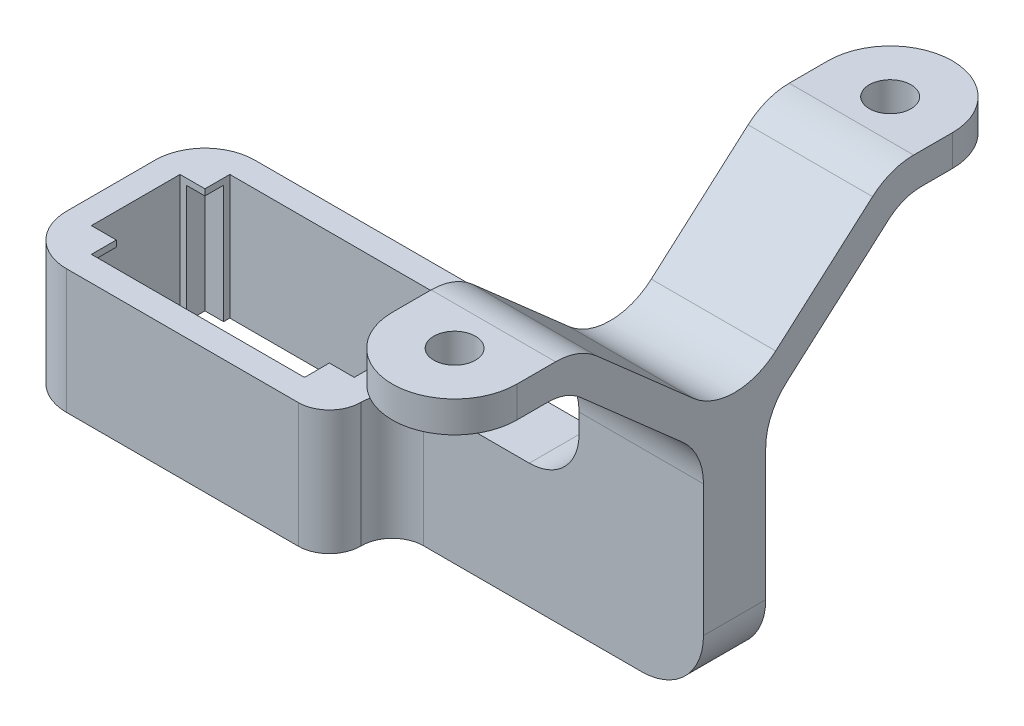
SolidWorks part; units mm, degrees
material "Nylon 101"
ref_plane "Front Plane" through (0, 0, 0) normal (0, 0, 1) x (1, 0, 0)
ref_plane "Top Plane" through (0, 0, 0) normal (0, 1, 0) x (1, 0, 0)
ref_plane "Right Plane" through (0, 0, 0) normal (1, 0, 0) x (0, 0, -1)
sketch "Sketch1" plane through (0, 20.13, 0) normal (0, 1, 0) x (1, 0, 0)
  line L0 (20.125, 10.125) -> (17.125, 10.125)
  line L1 (-20.125, 10.125) -> (-20.125, 7.125)
  line L2 (-20.125, -10.125) -> (-17.125, -10.125)
  line L3 (20.125, -10.125) -> (20.125, -7.125)
  line L4 (20.075, -10.075) -> (20.075, 10.075)
  line L5 (20.075, 10.075) -> (-20.075, 10.075)
  line L6 (-20.075, 10.075) -> (-20.075, -10.075)
  line L7 (-20.075, -10.075) -> (20.075, -10.075)
  line L10 (-20.075, 10.075) -> (-20.075, -10.075) construction
  line L12 (25.125, -15.125) -> (25.125, 15.125)
  line L13 (25.125, 15.125) -> (-25.125, 15.125)
  line L14 (-25.125, 15.125) -> (-25.125, -15.125)
  line L15 (-25.125, -15.125) -> (25.125, -15.125)
  line L16 (20.125, 7.125) -> (20.125, 10.125)
  line L17 (20.125, 7.125) -> (21.125, 7.125)
  line L19 (20.125, -7.125) -> (21.125, -7.125)
  line L20 (21.125, 7.125) -> (21.125, -7.125)
  line L21 (-20.125, 7.125) -> (-21.125, 7.125)
  line L23 (-20.125, -7.125) -> (-21.125, -7.125)
  line L24 (-21.125, 7.125) -> (-21.125, -7.125)
  line L26 (-17.125, 10.125) -> (-17.125, 11.125)
  line L27 (-17.125, 11.125) -> (17.125, 11.125)
  line L28 (17.125, 10.125) -> (17.125, 11.125)
  line L30 (17.125, -10.125) -> (17.125, -11.125)
  line L31 (17.125, -11.125) -> (-17.125, -11.125)
  line L32 (-17.125, -10.125) -> (-17.125, -11.125)
  line L33 (20.075, -10.075) -> (20.075, 10.075) construction
  line L34 (20.125, -10.125) -> (20.125, 10.125) construction
  line L35 (-20.075, -10.075) -> (20.075, -10.075) construction
  line L36 (17.125, -10.125) -> (20.125, -10.125)
  line L37 (-20.125, -10.125) -> (20.125, -10.125) construction
  line L38 (20.075, 10.075) -> (-20.075, 10.075) construction
  line L39 (-17.125, 10.125) -> (-20.125, 10.125)
  line L40 (20.125, 10.125) -> (-20.125, 10.125) construction
  line L41 (-20.125, -7.125) -> (-20.125, -10.125)
  line L42 (-20.125, 10.125) -> (-20.125, -10.125) construction
  dimension "D4" = 1
  dimension "D5" = 3
  dimension "D1" = 0
  dimension "D2" = 0.05
  dimension "D3" = 5
extrude "Boss-Extrude1" add sketch "Sketch1" against normal blind 19 and the other way blind 1
ref_plane "Plane1" through (0, 0, 0) normal (0, 0, 1) x (1, 0, 0)
sketch "Sketch2" plane through (0, 0, 0) normal (0, 0, 1) x (1, 0, 0)
  line L0 (25.125, 21.13) -> (55.125, 21.13)
  line L1 (55.125, 21.13) -> (55.125, 61.13)
  line L2 (55.125, 61.13) -> (75.125, 61.13)
  line L3 (75.125, 61.13) -> (75.125, 1.13)
  line L4 (75.125, 1.13) -> (25.125, 1.13)
  line L5 (25.125, 1.13) -> (25.125, 21.13) construction
  line L6 (25.125, 21.13) -> (25.125, 1.13)
  dimension "D1" = 50
  dimension "D2" = 60
extrude "Boss-Extrude2" add sketch "Sketch2" against normal mid plane 10
sketch "Sketch3" plane through (0, 61.13, 0) normal (0, 1, 0) x (1, 0, 0)
  line L0 (65.125, 35) -> (65.125, -35) construction
  line L1 (75.125, 35) -> (75.125, -35)
  line L2 (55.125, 35) -> (55.125, -35)
  line L3 (55.125, 5) -> (55.125, -5) construction
  line L6 (65.125, 5) -> (65.125, -5) construction
  line L7 (75.125, 5) -> (55.125, 5) construction
  line L8 (75.125, -5) -> (55.125, -5) construction
  line L9 (75.125, 5) -> (75.125, -5) construction
  line L10 (55.125, 5) -> (55.125, -5)
  line L11 (75.125, 5) -> (75.125, -5)
  arc A0 (75.125, 35) -> (55.125, 35) centre (65.125, 35) ccw
  arc A1 (55.125, -35) -> (75.125, -35) centre (65.125, -35) ccw
  point P2 (65.125, 0)
  point P7 (65.125, 0)
  line M8 (75.125, 5) -> (55.125, 5)
  line M10 (55.125, -5) -> (75.125, -5)
  dimension "D1" = 70
extrude "Boss-Extrude3" add sketch "Sketch3" against normal blind 5 contours L1 A0 L2 M8 | L2 A1 L1 M10
sketch "Sketch4" plane through (0, 56.13, 0) normal (0, -1, 0) x (1, 0, 0)
  circle A0 centre (65.125, 35) radius 3.35
  circle A1 centre (65.125, -35) radius 3.35
  dimension "D1" = 6.7
extrude "Cut-Extrude1" cut sketch "Sketch4" against normal blind 10
sketch "Sketch6" plane through (0, 21.13, 0) normal (0, 1, 0) x (1, 0, 0)
  line L0 (17.125, 11.125) -> (-17.125, 11.125) construction
  line L1 (21.125, 11.125) -> (17.125, 11.125)
  line L2 (21.125, 11.125) -> (21.125, 7.125)
  line L3 (21.125, 7.125) -> (17.125, 7.125)
  line L4 (17.125, 11.125) -> (17.125, 7.125)
  line L5 (21.125, -11.125) -> (17.125, -11.125)
  line L6 (21.125, -11.125) -> (21.125, -7.125)
  line L7 (21.125, -7.125) -> (17.125, -7.125)
  line L8 (17.125, -11.125) -> (17.125, -7.125)
  line L9 (-21.125, -11.125) -> (-17.125, -11.125)
  line L10 (-21.125, -11.125) -> (-21.125, -7.125)
  line L11 (-21.125, -7.125) -> (-17.125, -7.125)
  line L12 (-17.125, -11.125) -> (-17.125, -7.125)
  line L13 (-21.125, 11.125) -> (-17.125, 11.125)
  line L14 (-21.125, 11.125) -> (-21.125, 7.125)
  line L15 (-21.125, 7.125) -> (-17.125, 7.125)
  line L16 (-17.125, 11.125) -> (-17.125, 7.125)
  line L17 (21.125, -7.125) -> (21.125, 7.125) construction
  line L18 (-17.125, -11.125) -> (17.125, -11.125) construction
  line L19 (-21.125, 7.125) -> (-21.125, -7.125) construction
  line L20 (21.125, 7.125) -> (20.125, 7.125) construction
  line L21 (17.125, 10.125) -> (17.125, 11.125) construction
extrude "Boss-Extrude4" add sketch "Sketch6" against normal blind 1
sketch "Sketch10" plane through (0, 1.13, 0) normal (0, -1, 0) x (1, 0, 0)
  line L1 (21.125, 7.125) -> (21.125, -7.125) construction
  line L2 (21.125, 0) -> (24.125, 0) construction
  circle A0 centre (24.125, 0) radius 2
  circle A1 centre (24.125, 0) radius 3.5
  dimension "D1" = 4
  dimension "D2" = 7
  dimension "D3" = 1
hole_wizard "Tap Drill for M4x0.7 Tap1" positions "Sketch11" profile "Sketch12" hole size "M4x0.7" standard "ANSI Metric" end condition through all
sketch "Sketch11" plane through (0, 1.13, 0) normal (0, -1, 0) x (-1, 0, 0)
  point P0 (-24.125, 0)
sketch "Sketch12" plane through (24.125, 1.13, 0) normal (1, 0, 0) x (0, 0, -1)
  line L0 (0, 0) -> (0, 60)
  line L1 (0, 60) -> (1.65, 60)
  line L2 (1.65, 60) -> (1.65, 0.025)
  line L3 (1.65, 0.025) -> (1.675, 0)
  line L5 (1.675, 0) -> (0, 0)
  line L6 (-1.65, 0.025) -> (-1.675, 0) construction
  line L11 (0, -6.35) -> (0, 107.95) construction
  dimension "Thru Hole Dia." = 3.3
  dimension "Thru Hole Depth" = 60
  dimension "Near C'Sink Dia." = 3.35
  dimension "Near C'Sink Angle" = 90
sketch "Sketch13" plane through (0, 61.13, 0) normal (0, 1, 0) x (1, 0, 0)
  line L0 (55.125, 35) -> (55.125, -35) construction
  line L1 (55.125, 35) -> (55.125, -35)
  line L2 (75.125, 35) -> (75.125, -35) construction
  line L3 (75.125, 35) -> (75.125, -35)
  line L5 (55.125, -25) -> (75.125, -25)
  line L6 (55.125, -25) -> (55.125, 25)
  line L7 (55.125, 25) -> (75.125, 25)
  line L8 (75.125, -25) -> (75.125, 25)
  line L9 (55.125, -25) -> (75.125, 25) construction
  line L10 (55.125, 25) -> (75.125, -25) construction
  point P4 (65.125, 0)
  dimension "D1" = 10
  dimension "D2" = 10
extrude "Cut-Extrude2" cut sketch "Sketch13" against normal blind 22 contours L7 L1 L5 L3
sketch "Sketch14" plane through (75.125, 0, 0) normal (1, 0, 0) x (0, 0, -1)
  line L1 (25, 56.13) -> (25, 61.13)
  line L2 (25, 61.13) -> (0, 39.13)
  line L3 (-5, 39.13) -> (5, 39.13) construction
  line L8 (25, 56.13) -> (27, 56.13)
  line L9 (35, 56.13) -> (25, 56.13) construction
  line L10 (27, 56.13) -> (5, 36.77)
  line L11 (5, 1.13) -> (5, 39.13) construction
  line L12 (5, 36.77) -> (-5, 36.77)
  line L13 (0, 36.77) -> (0, 39.13)
  line L14 (-27, 56.13) -> (-5, 36.77)
  line L15 (-25, 56.13) -> (-27, 56.13)
  line L16 (-25, 61.13) -> (0, 39.13)
  line L17 (-25, 56.13) -> (-25, 61.13)
  line M2 (5, 39.13) -> (-5, 39.13)
  line M3 (-5, 39.13) -> (-5, 1.13)
  line M5 (5, 1.13) -> (5, 39.13)
  dimension "D1" = 2
extrude "Boss-Extrude5" add sketch "Sketch14" against normal up to surface (20 mm away) contours L10 L8 L1 L2 M2 M5 | L17 L15 L14 L16 M3 M2 up to face at (55.125, 30.13, 0)
fillet "Fillet1" radius 10 6 edges at (75.125, 1.13, 0) (65.125, 36.77, -5) (65.125, 39.13, 0) (65.125, 61.13, -25) (65.125, 36.77, 5) (65.125, 61.13, 25)
fillet "Fillet2" radius 8 2 edges at (65.125, 56.13, 27) (65.125, 56.13, -27)
fillet "Fillet3" radius 5 4 edges at (25.125, 11.13, 15.125) (25.125, 11.13, 5) (25.125, 11.13, -15.125) (25.125, 11.13, -5)
fillet "Fillet4" radius 8 3 edges at (-25.125, 11.13, 15.125) (-25.125, 11.13, -15.125) (55.125, 21.13, 0)
